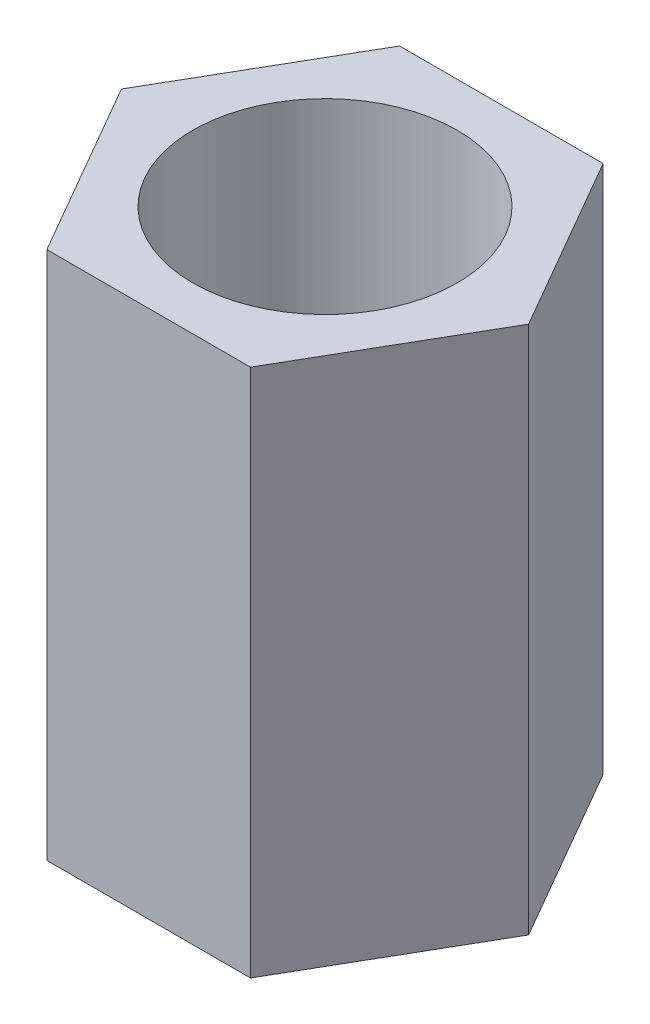
SolidWorks part; units mm, degrees
ref_plane "Alzado" through (0, 0, 0) normal (0, 0, 1) x (1, 0, 0)
ref_plane "Planta" through (0, 0, 0) normal (0, 1, 0) x (1, 0, 0)
ref_plane "Vista lateral" through (0, 0, 0) normal (1, 0, 0) x (0, 0, -1)
sketch "Croquis1" plane through (0, 0, 0) normal (0, 1, 0) x (1, 0, 0)
  line L1 (1.1547, 2) -> (-1.1547, 2)
  line L2 (-1.1547, 2) -> (-2.3094, 0)
  line L3 (-2.3094, 0) -> (-1.1547, -2)
  line L4 (-1.1547, -2) -> (1.1547, -2)
  line L5 (1.1547, -2) -> (2.3094, 0)
  line L6 (2.3094, 0) -> (1.1547, 2)
  circle A0 centre (0, 0) radius 2 construction
  circle A1 centre (0, 0) radius 1.5
  dimension "D1" = 4
  dimension "D2" = 3
extrude "Saliente-Extruir1" add sketch "Croquis1" along normal mid plane 6
scale "Scale1" scale about centroid uniform scaling yes scale factor 0.888889
